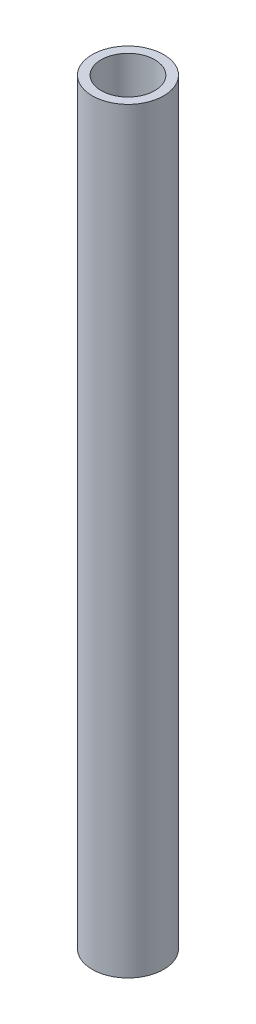
SolidWorks part; units mm, degrees
ref_plane "Front Plane" through (0, 0, 0) normal (0, 0, 1) x (1, 0, 0)
ref_plane "Top Plane" through (0, 0, 0) normal (0, 1, 0) x (1, 0, 0)
ref_plane "Right Plane" through (0, 0, 0) normal (1, 0, 0) x (0, 0, -1)
sketch "Sketch1" plane through (0, 0, 0) normal (0, 1, 0) x (1, 0, 0)
  circle A0 centre (0, 0) radius 12
extrude "Boss-Extrude1" add sketch "Sketch1" along normal blind 254 contours A0
sketch "Sketch2" plane through (0, 254, 0) normal (0, 1, 0) x (1, 0, 0)
  circle A0 centre (0, 0) radius 9
extrude "Cut-Extrude1" cut sketch "Sketch2" against normal blind 254
